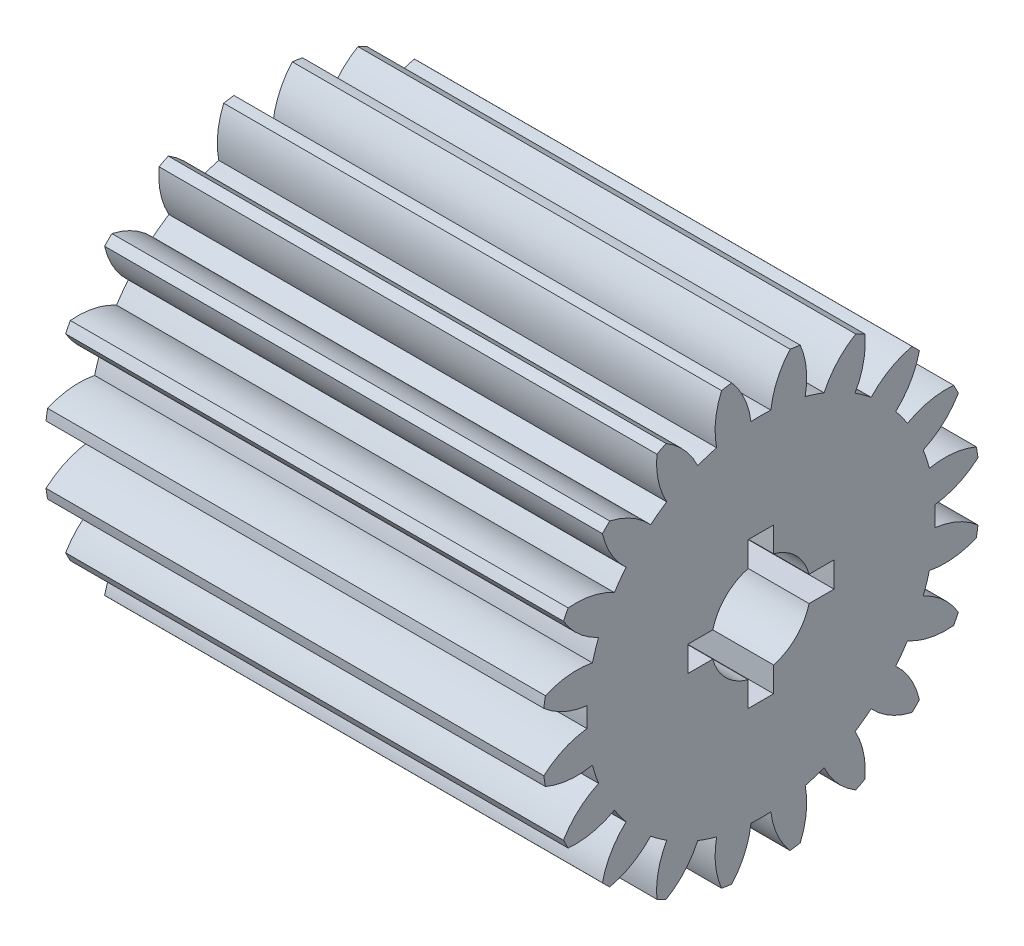
SolidWorks part; units mm, degrees
material "AISI 1020"
ref_plane "Plane1" through (0, 0, 0) normal (0, 0, 1) x (1, 0, 0)
ref_plane "Plane2" through (0, 0, 0) normal (0, 1, 0) x (1, 0, 0)
ref_plane "Plane3" through (0, 0, 0) normal (1, 0, 0) x (0, 0, -1)
other "Configuration Table"
sketch "HoldingSke" plane through (0, 0, 0) normal (0, 1, 0) x (1, 0, 0)
  line L0 (0, 0) -> (2.3492, -0.8551)
  line L1 (-15, 0) -> (100, 0) construction
  line L2 (0, 0) -> (-2.1039, 2.3779)
  line L3 (0, 0) -> (-11.863, 4.5341)
  line L4 (0, 0) -> (8.1152, 2.9537)
  line L5 (0, 0) -> (-46.8476, -17.4728)
  line L6 (0, 0) -> (-8.2896, -5.593)
  line L7 (-2.1039, 2.3779) -> (8.6586, 51.2059)
  line L8 (-76.2, 54.61) -> (-75.9, 54.61)
  line L9 (-71.009, 38.7566) -> (-53.1078, 45.2721)
  line L10 (-76.2, 71.12) -> (104.1128, 71.12)
  line L11 (0, 0) -> (-10, 0)
  line L12 (-76.2, 101.6) -> (-76.185, 101.6)
  line L13 (24.9733, 27.94) -> (52.9518, 28.4284)
  line L14 (24.9733, 27.94) -> (24.9743, 27.94)
  line L15 (24.9733, 27.94) -> (100.4006, 29.5858)
  line L16 (-63.627, -0.4) -> (-12.827, -0.4)
  circle A0 centre (0, 0) radius 1
  circle A1 centre (0, 0) radius 3.499
  circle A2 centre (0, 0) radius 37.5
  circle A3 centre (0, 0) radius 1
  dimension "MHD" = 6.998
  dimension "Hub_dia" = 75
  dimension "Bore" = 2
  dimension "MBD" = 2
  dimension "Num_teeth" = 20
  dimension "Pitch" = 2.5
  dimension "Overall_len" = 50
  dimension "Show_teeth" = 20
  dimension "Thickness" = 10
  dimension "OAL" = 50.0001
  dimension "T_dim" = 0.3
  dimension "Ap" = 20
  dimension "H" = 19.05
  dimension "Pitch_radius" = 180.3128
  dimension "Width" = 10
  dimension "Backlash" = 0.015
  dimension "Addendum_fac" = 1
  dimension "Dedendum_fac" = 1.25
  dimension "Clearance_fac" = 0.25
  dimension "Dedendum_add" = 0.001
  dimension "Module" = 0.4
sketch "BasProSke" plane through (0, 0, 0) normal (0, 1, 0) x (1, 0, 0)
  line L0 (-10, 0) -> (60, 0) construction
  line L1 (0, 0) -> (0, 4.4)
  line L2 (0, 0) -> (10, 0)
  line L3 (10, 0) -> (10, 4.4)
  line L4 (10, 4.4) -> (0, 4.4)
  dimension "Thickness" = 10
  dimension "Diameter" = 8.8
revolve "Base-Revolve" add sketch "BasProSke" angle 360 about L0
sketch "TooCutSke" plane through (0, 0, 0) normal (1, 0, 0) x (0, 0, -1)
  line L1 (0, 0) -> (0, 107) construction
  line L2 (0, 0) -> (-0.3401, 3.9855) construction
  line L3 (0, 0) -> (-1.2482, 7.8811) construction
  line L4 (-0.3401, 3.9855) -> (-0.6241, 3.9405) construction
  arc A0 (0.1996, 3.4933) -> (-0.1996, 3.4933) centre (0, 0) ccw
  arc A1 (0.606, 4.3837) -> (-0.606, 4.3837) centre (0, 0) ccw
  circle A2 centre (0, 0) radius 4 construction
  circle A3 centre (0, 0) radius 3.7588 construction
  arc A4 (-0.1996, 3.4933) -> (-0.606, 4.3837) centre (-1.7886, 3.306) ccw
  arc A5 (0.606, 4.3837) -> (0.1996, 3.4933) centre (1.7886, 3.306) ccw
  dimension "Root_dia" = 6.998
  dimension "Overcut_dia" = 8.8508
  dimension "Pitch_dia" = 8
  dimension "Base_dia" = 7.5175
  dimension "Flank_rad" = 1.6
  dimension "Half_ang" = 9
  dimension "Half_CT" = 0.2876
extrude "ToothCut" cut sketch "TooCutSke" along normal through all
fillet "Breaks" [suppressed] radius 0.008
fillet "RootFillets" [suppressed] radius 0.101
pattern_circular "TeethCuts" count 20 every 18 about axis through (-10, 0, 0) along (1, 0, 0) of "ToothCut", "Breaks", "RootFillets"
sketch "HubNeaOneSke" plane through (0, 0, 0) normal (-1, 0, 0) x (0, 0, 1)
  circle A0 centre (0, 0) radius 3.499
  dimension "Diameter" = 6.998
extrude "HubNearOne" [suppressed] add sketch "HubNeaOneSke" along normal blind 40.0001
sketch "HubNeaBotSke" plane through (0, 0, 0) normal (-1, 0, 0) x (0, 0, 1)
  circle A0 centre (0, 0) radius 3.499
  dimension "Diameter" = 6.998
extrude "HubNearBoth" [suppressed] add sketch "HubNeaBotSke" along normal blind 20
ref_plane "FarPln" through (10, 0, 0) normal (1, 0, 0) x (0, 0, -1)
sketch "HubFarSke" plane through (10, 0, 0) normal (1, 0, 0) x (0, 0, -1)
  circle A0 centre (0, 0) radius 3.499
  dimension "Diameter" = 6.998
extrude "HubFar" [suppressed] add sketch "HubFarSke" along normal blind 20
sketch "BorSke" plane through (0, 0, 0) normal (1, 0, 0) x (0, 0, -1)
  circle A0 centre (0, 0) radius 1
  dimension "Diameter" = 2
extrude "Bore" cut sketch "BorSke" along normal mid plane 100.0001
sketch "KeySke" plane through (0, 0, 0) normal (1, 0, 0) x (0, 0, -1)
  line L0 (-0.4, 0) -> (-0.4, 1.3)
  line L1 (-0.4, 1.3) -> (0.4, 1.3)
  line L2 (0.4, 1.3) -> (0.4, 0)
  line L3 (0, 0) -> (0, 34) construction
  line L4 (-0.4, 0) -> (0.4, 0)
  dimension "Offset" = 1.3
  dimension "Width" = 0.8
extrude "Keyway" [suppressed] cut sketch "KeySke" along normal mid plane 100.0001
pattern_circular "Keyway2" [suppressed] count 2 every 90 about axis through (-10, 0, 0) along (1, 0, 0)
sketch "Sketch1" plane through (10, 0, 0) normal (1, 0, 0) x (0, 0, -1)
  line L0 (-0.255, 0.9587) -> (0.255, 0.9587)
  line L1 (-0.255, 0.9587) -> (-0.255, 1.4687)
  line L2 (0.255, 0.9587) -> (0.255, 1.4687)
  line L3 (-0.255, 1.4687) -> (0.255, 1.4687)
  line L4 (0.9587, 0.255) -> (0.9587, -0.255)
  line L5 (0.9587, 0.255) -> (1.4687, 0.255)
  line L6 (0.9587, -0.255) -> (1.4687, -0.255)
  line L7 (1.4687, 0.255) -> (1.4687, -0.255)
  line L8 (0.255, -0.9587) -> (-0.255, -0.9587)
  line L9 (0.255, -0.9587) -> (0.255, -1.4687)
  line L10 (-0.255, -0.9587) -> (-0.255, -1.4687)
  line L11 (0.255, -1.4687) -> (-0.255, -1.4687)
  line L12 (-0.9587, -0.255) -> (-0.9587, 0.255)
  line L13 (-0.9587, -0.255) -> (-1.4687, -0.255)
  line L14 (-0.9587, 0.255) -> (-1.4687, 0.255)
  line L15 (-1.4687, -0.255) -> (-1.4687, 0.255)
  circle A0 centre (0, 0) radius 0.992
  dimension "D2" = 1.984
  dimension "D1" = 0.51
  dimension "D3" = 0.51
  dimension "D4" = 0.51
  dimension "D5" = 0.51
  dimension "D6" = 0.51
  dimension "D7" = 0.51
  dimension "D8" = 0.51
  dimension "D9" = 0.51
extrude "Cut-Extrude1" cut sketch "Sketch1" against normal blind 100 contours L3 L2 L0 L1 | L5 L7 L6 L4 | L9 L11 L10 L8 | L13 L15 L14 L12
equation "' \"Module@HoldingSke\" = 6.35"
equation "' \"Num_teeth@HoldingSke\" = 12"
equation "' \"Ap@HoldingSke\" =  20"
equation "' \"Ap@HoldingSke\" = 20"
equation "' \"Width@HoldingSke\" = 0.5 * 25.4"
equation "' \"Hub_dia@HoldingSke\"= 1 * 25.4"
equation "' \"Hub_dia@HoldingSke\" = 1 * 25.4"
equation "' \"Overall_len@HoldingSke\" = 1.0 * 25.4"
equation "' \"Bore@HoldingSke\" = 0.75 * 25.4"
equation "' \"T_dim@HoldingSke\" = 0.1 * 25.4"
equation "' \"Width@KeySke\" = 0.25 * 25.4"
equation "' \"Show_teeth@HoldingSke\" = 13"
equation "' \"Backlash@HoldingSke\" = 0.009 * 25.4"
equation "' \"Addendum_fac@HoldingSke\" = 1.0"
equation "' \"Dedendum_fac@HoldingSke\" = 1.25"
equation "' \"Dedendum_add@HoldingSke\" = 0.00005 * 25.4"
equation "' \"Clearance_fac@HoldingSke\" = 0.25"
equation "\"Pitch@HoldingSke\" = 1 / \"Module@HoldingSke\""
equation "\"Overcut_dia@TooCutSke\" = (\"Num_teeth@HoldingSke\" + 2 * \"Addendum_fac@HoldingSke\") / \"Pitch@HoldingSke\" + 0.002 * 25.4"
equation "\"Pitch_dia@TooCutSke\" = \"Num_teeth@HoldingSke\" / \"Pitch@HoldingSke\""
equation "\"Base_dia@TooCutSke\" = \"Num_teeth@HoldingSke\" / \"Pitch@HoldingSke\" * cos((\"Ap@HoldingSke\"  * 3.14159265 / 180))"
equation "\"Root_dia@TooCutSke\" = (\"Num_teeth@HoldingSke\" + 2) / \"Pitch@HoldingSke\" - 2 * (\"Addendum_fac@HoldingSke\" + \"Dedendum_fac@HoldingSke\") / \"Pitch@HoldingSke\" - \"Dedendum_add@HoldingSke\" * 2"
equation "\"Half_ang@TooCutSke\" = 180 / \"Num_teeth@HoldingSke\""
equation "\"Half_CT@TooCutSke\" = \"Num_teeth@HoldingSke\" / \"Pitch@HoldingSke\" * sin((3.14159265 / 2 / \"Num_teeth@HoldingSke\")) / 2 - 7 * \"Backlash@HoldingSke\" / 4"
equation "\"Flank_rad@TooCutSke\" = \"Num_teeth@HoldingSke\" / \"Pitch@HoldingSke\" / 5"
equation "\"Radius@RootFillets\" = \"Clearance_fac@HoldingSke\" / \"Pitch@HoldingSke\" + \"Dedendum_add@HoldingSke\""
equation "\"Break_rad@Breaks\" = 0.02 / \"Pitch@HoldingSke\""
equation "\"Thickness@HoldingSke\" = \"Width@HoldingSke\""
equation "\"OAL@HoldingSke\" = \"Thickness@HoldingSke\""
equation "\"MHD@HoldingSke\" = (\"Num_teeth@HoldingSke\" + 2) / \"Pitch@HoldingSke\" - 2 * (\"Addendum_fac@HoldingSke\" + \"Dedendum_fac@HoldingSke\")  / \"Pitch@HoldingSke\" - \"Dedendum_add@HoldingSke\" * 2"
equation "\"MBD@HoldingSke\" = (\"Num_teeth@HoldingSke\" + 2) / \"Pitch@HoldingSke\" - 2 * (\"Addendum_fac@HoldingSke\" + \"Dedendum_fac@HoldingSke\")  / \"Pitch@HoldingSke\" - \"Dedendum_add@HoldingSke\" * 2 - 0.002 * 25.4"
equation "\"MHD@HoldingSke\" = ((sgn( \"MHD@HoldingSke\" - \"Hub_dia@HoldingSke\" )-1)*( \"MHD@HoldingSke\" - \"Hub_dia@HoldingSke\" ))/-2+ \"Hub_dia@HoldingSke\""
equation "\"MBD@HoldingSke\" = ((sgn( \"MBD@HoldingSke\" - \"Bore@HoldingSke\" )-1)*( \"MBD@HoldingSke\" - \"Bore@HoldingSke\" ))/-2+ \"Bore@HoldingSke\""
equation "\"OAL@HoldingSke\" = ((sgn( \"OAL@HoldingSke\" - \"Overall_len@HoldingSke\" )+1)*( \"OAL@HoldingSke\" - \"Overall_len@HoldingSke\" ))/2 + \"Overall_len@HoldingSke\" + 0.000002 * 25.4"
equation "\"Num_teeth@TeethCuts\" = int( \"Show_teeth@HoldingSke\" ) + 1"
equation "\"Num_teeth@TeethCuts\" = ((sgn( \"Num_teeth@TeethCuts\" - \"Num_teeth@HoldingSke\" )-1)*( \"Num_teeth@TeethCuts\" - \"Num_teeth@HoldingSke\" ))/-2+ \"Num_teeth@HoldingSke\""
equation "\"Num_teeth@TeethCuts\" = ((sgn( \"Num_teeth@TeethCuts\" - 2.0)+1)*( \"Num_teeth@TeethCuts\" - 2.0))/2 +2.0"
equation "\"Angle@TeethCuts\" = 360.0 / \"Num_teeth@HoldingSke\""
equation "\"Diameter@BasProSke\" = (\"Num_teeth@HoldingSke\" + 2 * \"Addendum_fac@HoldingSke\") / \"Pitch@HoldingSke\""
equation "\"Thickness@BasProSke\"  = \"Thickness@HoldingSke\""
equation "' \"Fillet_rad@BasProSke\" =  \"Thickness@HoldingSke\" * 0.05"
equation "' \"Fillet_rad@BasProSke\" = \"Thickness@HoldingSke\" * 0.05"
equation "\"MHD@HoldingSke\" = ((sgn( \"MHD@HoldingSke\" - \"Root_dia@TooCutSke\" )-1)*( \"MHD@HoldingSke\" - \"Root_dia@TooCutSke\" ))/-2+ \"Root_dia@TooCutSke\""
equation "\"Diameter@HubNeaOneSke\" = \"MHD@HoldingSke\""
equation "\"Length@HubNearOne\" = \"OAL@HoldingSke\" - \"Thickness@BasProSke\""
equation "\"Diameter@HubNeaBotSke\" = \"MHD@HoldingSke\""
equation "\"Length@HubNearBoth\" = ( \"OAL@HoldingSke\" - \"Thickness@BasProSke\" ) / 2.0"
equation "\"Thickness@FarPln\" = \"Thickness@BasProSke\""
equation "\"Diameter@HubFarSke\" = \"MHD@HoldingSke\""
equation "\"Length@HubFar\" = ( \"OAL@HoldingSke\" - \"Thickness@BasProSke\" ) / 2.0"
equation "\"Diameter@BorSke\" = \"MBD@HoldingSke\""
equation "\"D1@Bore\" = \"OAL@HoldingSke\" * 2.0"
equation "\"D1@Keyway\" = \"OAL@HoldingSke\" * 2.0"
equation "\"Offset@KeySke\" = \"T_dim@HoldingSke\" + \"MBD@HoldingSke\" / 2.0"
